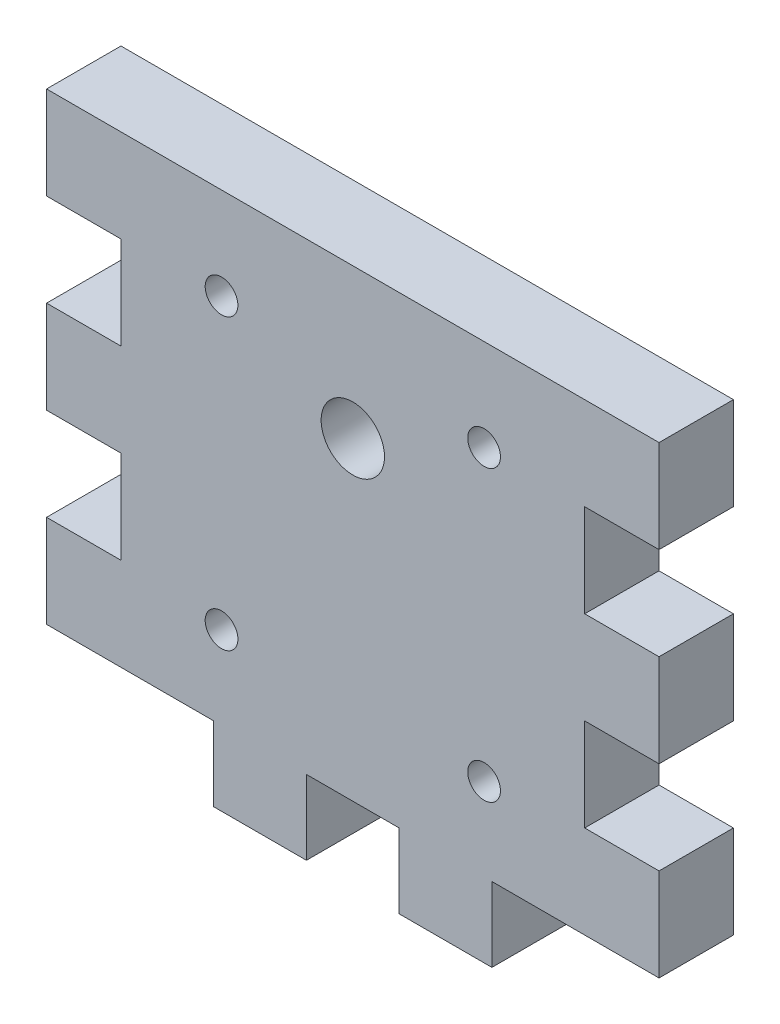
SolidWorks part; units mm, degrees
ref_plane "Front Plane" through (0, 0, 0) normal (0, 0, 1) x (1, 0, 0)
ref_plane "Top Plane" through (0, 0, 0) normal (0, 1, 0) x (1, 0, 0)
ref_plane "Right Plane" through (0, 0, 0) normal (1, 0, 0) x (0, 0, -1)
sketch "Sketch1" plane through (0, 0, 0) normal (0, 0, 1) x (1, 0, 0)
  line L0 (34.2226, -16.3431) -> (34.2226, -24.2607)
  line L1 (-11.7153, 7.4096) -> (40.5726, 7.4096)
  line L2 (-5.3653, -0.5079) -> (-5.3653, -8.4255)
  line L3 (-5.3653, -32.1783) -> (-11.7153, -32.1783)
  line L4 (34.2226, -0.5079) -> (34.2226, -8.4255)
  line L5 (14.4286, -25.1067) -> (14.4286, -32.1783) construction
  line L6 (2.5523, -38.5283) -> (2.5523, -32.1783)
  line L7 (2.5523, -32.1783) -> (-5.3653, -32.1783)
  line L8 (25.6364, -0.4229) -> (3.2209, -0.4229) construction
  line L9 (3.2209, -25.1067) -> (25.6364, -25.1067) construction
  line L10 (25.6364, -0.4229) -> (25.6364, -25.1067) construction
  line L11 (2.5523, -38.5283) -> (10.4698, -38.5283)
  line L12 (10.4698, -32.1783) -> (10.4698, -38.5283)
  line L13 (10.4698, -32.1783) -> (18.3874, -32.1783)
  line L14 (18.3874, -32.1783) -> (18.3874, -38.5283)
  line L15 (18.3874, -38.5283) -> (26.305, -38.5283)
  line L16 (26.305, -32.1783) -> (26.305, -38.5283)
  line L17 (3.2209, -0.4229) -> (3.2209, -25.1067) construction
  line L22 (26.305, -32.1783) -> (34.2226, -32.1783)
  line L23 (-5.3653, -24.2607) -> (-11.7153, -24.2607)
  line L24 (-11.7153, -32.1783) -> (-11.7153, -24.2607)
  line L25 (-5.3653, -16.3431) -> (-11.7153, -16.3431)
  line L27 (-5.3653, -8.4255) -> (-11.7153, -8.4255)
  line L28 (-11.7153, -16.3431) -> (-11.7153, -8.4255)
  line L30 (-5.3653, -16.3431) -> (-5.3653, -24.2607)
  line L31 (-5.3653, -0.5079) -> (-11.7153, -0.5079)
  line L32 (-11.7153, 7.4096) -> (-11.7153, -0.5079)
  line L35 (34.2226, -0.5079) -> (40.5726, -0.5079)
  line L36 (40.5726, 7.4096) -> (40.5726, -0.5079)
  line L37 (34.2226, -8.4255) -> (40.5726, -8.4255)
  line L39 (34.2226, -16.3431) -> (40.5726, -16.3431)
  line L40 (40.5726, -8.4255) -> (40.5726, -16.3431)
  line L41 (34.2226, -24.2607) -> (40.5726, -24.2607)
  line L43 (34.2226, -32.1783) -> (40.5726, -32.1783)
  line L44 (40.5726, -24.2607) -> (40.5726, -32.1783)
  circle A0 centre (3.2209, -0.4229) radius 1.397
  circle A1 centre (25.6364, -0.4229) radius 1.397
  circle A2 centre (25.6364, -25.1067) radius 1.397
  circle A3 centre (3.2209, -25.1067) radius 1.397
  circle A4 centre (14.4286, -5.3597) radius 2.7041
extrude "Boss-Extrude1" add sketch "Sketch1" along normal blind 6.35
